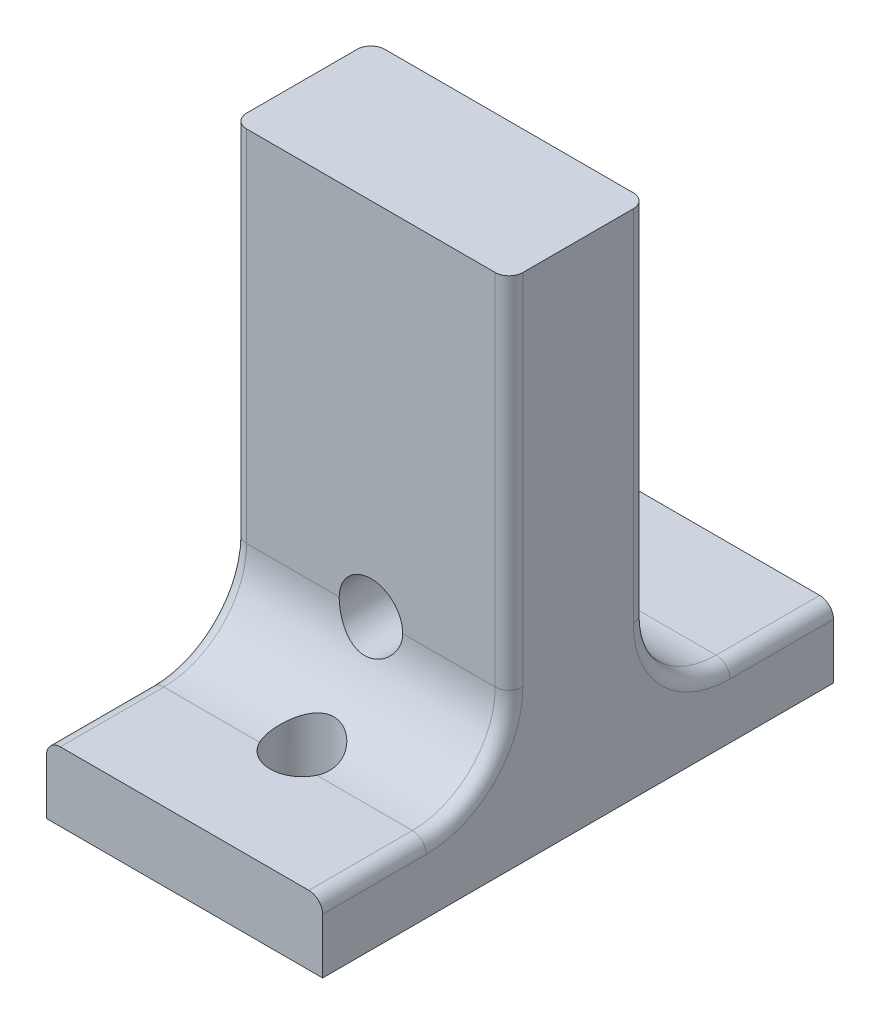
SolidWorks part; units mm, degrees
ref_plane "Front Plane" through (0, 0, 0) normal (0, 0, 1) x (1, 0, 0)
ref_plane "Top Plane" through (0, 0, 0) normal (0, 1, 0) x (1, 0, 0)
ref_plane "Right Plane" through (0, 0, 0) normal (1, 0, 0) x (0, 0, -1)
sketch "Sketch1" plane through (0, 0, 0) normal (1, 0, 0) x (0, 0, -1)
  line L0 (0, 0) -> (0, 46.99) construction
  line L1 (-6.35, 46.99) -> (6.35, 46.99)
  line L2 (6.35, 46.99) -> (6.35, 6.35)
  line L3 (6.35, 6.35) -> (23.495, 6.35)
  line L4 (23.495, 6.35) -> (23.495, 0)
  line L5 (23.495, 0) -> (-23.495, 0)
  line L6 (-23.495, 6.35) -> (-23.495, 0)
  line L7 (-6.35, 6.35) -> (-23.495, 6.35)
  line L8 (-6.35, 46.99) -> (-6.35, 6.35)
  dimension "D1" = 46.99
  dimension "D2" = 6.35
  dimension "D3" = 6.35
  dimension "D4" = 23.495
extrude "Boss-Extrude1" add sketch "Sketch1" along normal blind 25.4
fillet "Fillet1" radius 7.62 2 edges at (12.7, 6.35, 6.35) (12.7, 6.35, -6.35)
sketch "Sketch2" plane through (0, 0, 0) normal (0, -1, 0) x (1, 0, 0)
  line L0 (12.7, 23.495) -> (12.7, -23.495) construction
  line L1 (25.4, 23.495) -> (0, 23.495) construction
  line L2 (25.4, -23.495) -> (0, -23.495) construction
  line L3 (25.4, 0) -> (0, 0) construction
  line L4 (25.4, 23.495) -> (25.4, -23.495) construction
  circle A0 centre (12.7, 12.7) radius 2.921
  circle A1 centre (12.7, -12.7) radius 2.921
  dimension "D1" = 5.842
  dimension "D2" = 12.7
extrude "Cut-Extrude1" cut sketch "Sketch2" against normal through all
fillet "Fillet2" radius 1.27 12 edges at (0, 30.48, 6.35) (0, 8.5818, 8.5818) (0, 6.35, 18.7325) (25.4, 6.35, 18.7325) (25.4, 8.5818, 8.5818) (25.4, 30.48, 6.35) (0, 30.48, -6.35) (0, 8.5818, -8.5818) (0, 6.35, -18.7325) (25.4, 6.35, -18.7325) (25.4, 8.5818, -8.5818) (25.4, 30.48, -6.35)
sketch "Sketch3" plane through (0, 0, -6.35) normal (0, 0, -1) x (-1, 0, 0)
  line L0 (-12.7, 46.99) -> (-12.7, 13.97) construction
  line L1 (-24.13, 46.99) -> (-1.27, 46.99) construction
  line L2 (-24.13, 13.97) -> (-1.27, 13.97) construction
  circle A0 centre (-12.7, 13.97) radius 2.921
  dimension "D1" = 5.842
extrude "Cut-Extrude2" cut sketch "Sketch3" against normal through all both and the other way through all contours A0
